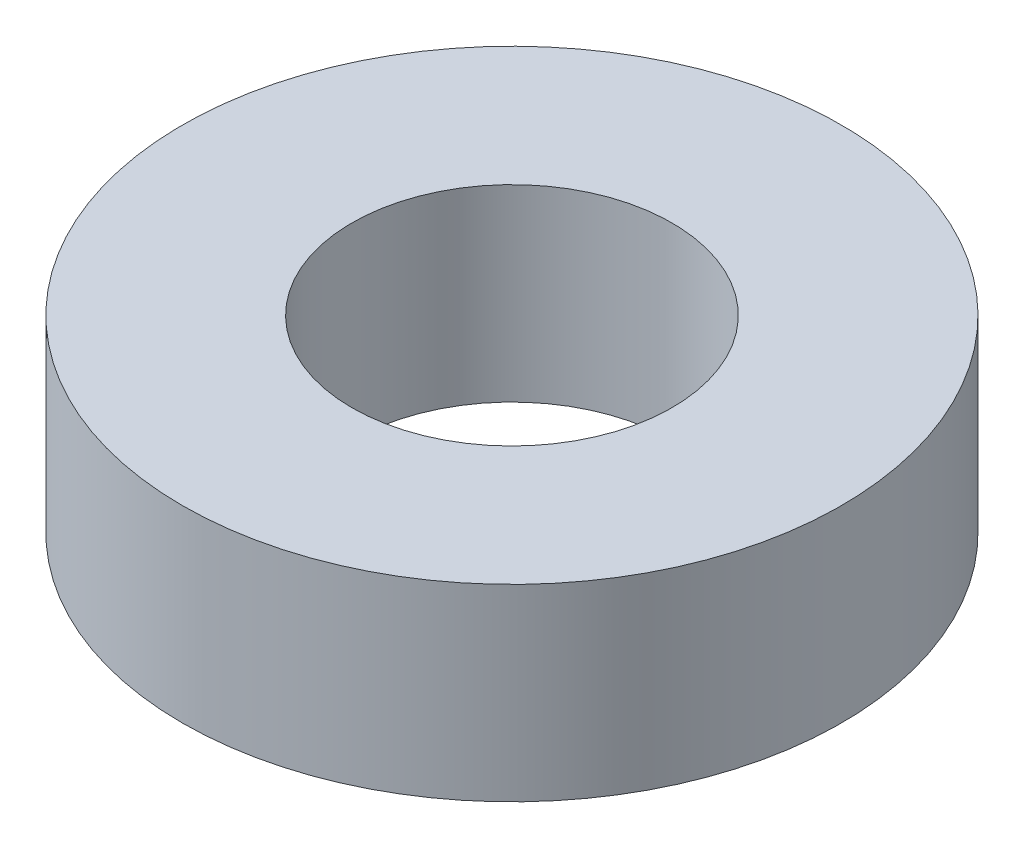
SolidWorks part; units mm, degrees
ref_plane "Front Plane" through (0, 0, 0) normal (0, 0, 1) x (1, 0, 0)
ref_plane "Top Plane" through (0, 0, 0) normal (0, 1, 0) x (1, 0, 0)
ref_plane "Right Plane" through (0, 0, 0) normal (1, 0, 0) x (0, 0, -1)
sketch "Sketch1" plane through (0, 0, 0) normal (0, 1, 0) x (1, 0, 0)
  circle A0 centre (0, 0) radius 8.5
  circle A1 centre (0, 0) radius 17.5
  dimension "D1" = 17
  dimension "D2" = 35
extrude "Boss-Extrude1" add sketch "Sketch1" along normal blind 10
